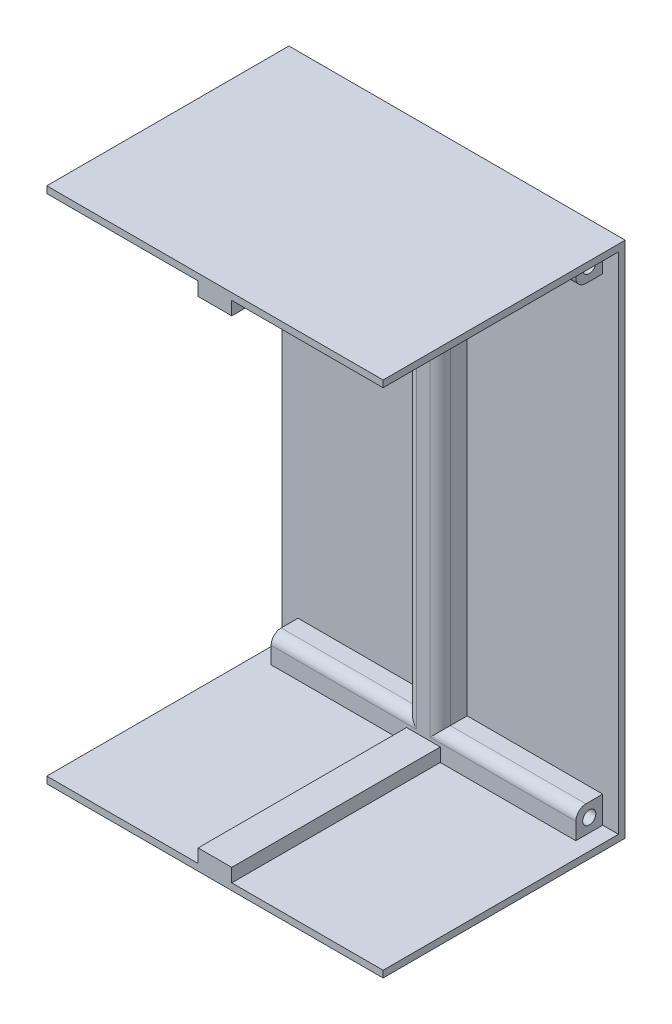
SolidWorks part; units mm, degrees
ref_plane "Front Plane" through (0, 0, 0) normal (1, 0, 0) x (0, 1, 0)
ref_plane "Top Plane" through (0, 0, 0) normal (0, 0, 1) x (0, 1, 0)
ref_plane "Right Plane" through (0, 0, 0) normal (0, 1, 0) x (-1, 0, 0)
sketch "Sketch1" plane through (0, 0, 0) normal (0, 0, 1) x (0, 1, 0)
  line L1 (0, 0) -> (154, 0)
  line L2 (0, 0) -> (0, 100)
  line L3 (0, 100) -> (154, 100)
  line L4 (154, 0) -> (154, 100)
  dimension "D1" = 154
  dimension "D2" = 100
extrude "Boss-Extrude1" add sketch "Sketch1" along normal blind 2
sketch "Sketch2" plane through (0, 0, 2) normal (0, 0, 1) x (1, 0, 0)
  line L0 (0, 0) -> (0, 154) construction
  line L1 (-100, 154) -> (0, 154)
  line L2 (-100, 154) -> (-100, 152)
  line L3 (-100, 152) -> (0, 152)
  line L4 (0, 154) -> (0, 152)
  line L5 (-100, 0) -> (0, 0)
  line L6 (-100, 0) -> (-100, 2)
  line L7 (-100, 2) -> (0, 2)
  line L8 (0, 0) -> (0, 2)
  dimension "D1" = 2
  dimension "D2" = 2
extrude "Boss-Extrude2" add sketch "Sketch2" along normal blind 70
sketch "Sketch3" plane through (0, 0, 2) normal (0, 0, 1) x (1, 0, 0)
  line L0 (-100, 152) -> (0, 152) construction
  line L1 (-95.3, 152) -> (-4.7, 152)
  line L2 (-95.3, 152) -> (-95.3, 144)
  line L3 (-95.3, 144) -> (-4.7, 144)
  line L4 (-4.7, 152) -> (-4.7, 144)
  line L5 (0, 2) -> (-100, 2) construction
  line L6 (-95.3, 2) -> (-4.7, 2)
  line L7 (-95.3, 2) -> (-95.3, 10)
  line L8 (-95.3, 10) -> (-4.7, 10)
  line L9 (-4.7, 2) -> (-4.7, 10)
  line L10 (-100, 152) -> (-100, 2) construction
  line L11 (0, 2) -> (0, 152) construction
  dimension "D1" = 4.7
  dimension "D2" = 4.7
  dimension "D3" = 8
  dimension "D4" = 8
extrude "Boss-Extrude3" add sketch "Sketch3" along normal blind 8
sketch "Sketch4" plane through (0, 0, 2) normal (0, 0, 1) x (1, 0, 0)
  line L0 (-95.3, 144) -> (-4.7, 144) construction
  line L1 (-55, 144) -> (-45, 144)
  line L2 (-55, 144) -> (-55, 10)
  line L3 (-55, 10) -> (-45, 10)
  line L4 (-45, 144) -> (-45, 10)
  line L5 (-4.7, 10) -> (-95.3, 10) construction
  line L6 (-100, 152) -> (-100, 2) construction
  line L7 (0, 2) -> (0, 152) construction
  dimension "D1" = 45
  dimension "D2" = 45
extrude "Boss-Extrude4" add sketch "Sketch4" along normal blind 8
sketch "Sketch5" plane through (0, 0, 10) normal (0, 0, 1) x (1, 0, 0)
  line L0 (-4.7, 152) -> (-95.3, 152) construction
  line L1 (-55, 152) -> (-45, 152)
  line L2 (-55, 152) -> (-55, 148)
  line L3 (-55, 148) -> (-45, 148)
  line L4 (-45, 152) -> (-45, 148)
  line L5 (-95.3, 2) -> (-4.7, 2) construction
  line L6 (-55, 2) -> (-45, 2)
  line L7 (-55, 2) -> (-55, 6)
  line L8 (-55, 6) -> (-45, 6)
  line L9 (-45, 2) -> (-45, 6)
  line L10 (-100, 152) -> (-100, 2) construction
  line L11 (0, 2) -> (0, 152) construction
  dimension "D1" = 45
  dimension "D2" = 45
  dimension "D3" = 4
  dimension "D4" = 4
extrude "Boss-Extrude5" add sketch "Sketch5" along normal blind 62
sketch "Sketch6" plane through (-95.3, 0, 0) normal (-1, 0, 0) x (0, -1, 0)
  line L0 (-152, 2) -> (-2, 2) construction
  line L1 (-2, 10) -> (-2, 2) construction
  circle A0 centre (-6, 6) radius 1.95
  point P6 (-2.6991, 6.4186)
  dimension "D3" = 3.9
  dimension "D1" = 4
  dimension "D2" = 4
extrude "Cut-Extrude1" cut sketch "Sketch6" against normal through all
sketch "Sketch7" plane through (-95.3, 0, 0) normal (-1, 0, 0) x (0, -1, 0)
  line L0 (-152, 72) -> (-152, 2) construction
  line L1 (-152, 2) -> (-2, 2) construction
  circle A0 centre (-148, 6) radius 1.95
  dimension "D1" = 3.9
  dimension "D2" = 4
  dimension "D3" = 4
extrude "Cut-Extrude2" cut sketch "Sketch7" against normal through all
fillet "Fillet1" radius 3 6 edges at (-75.15, 144, 10) (-24.85, 144, 10) (-24.85, 10, 10) (-75.15, 10, 10) (-45, 77, 10) (-55, 77, 10)
